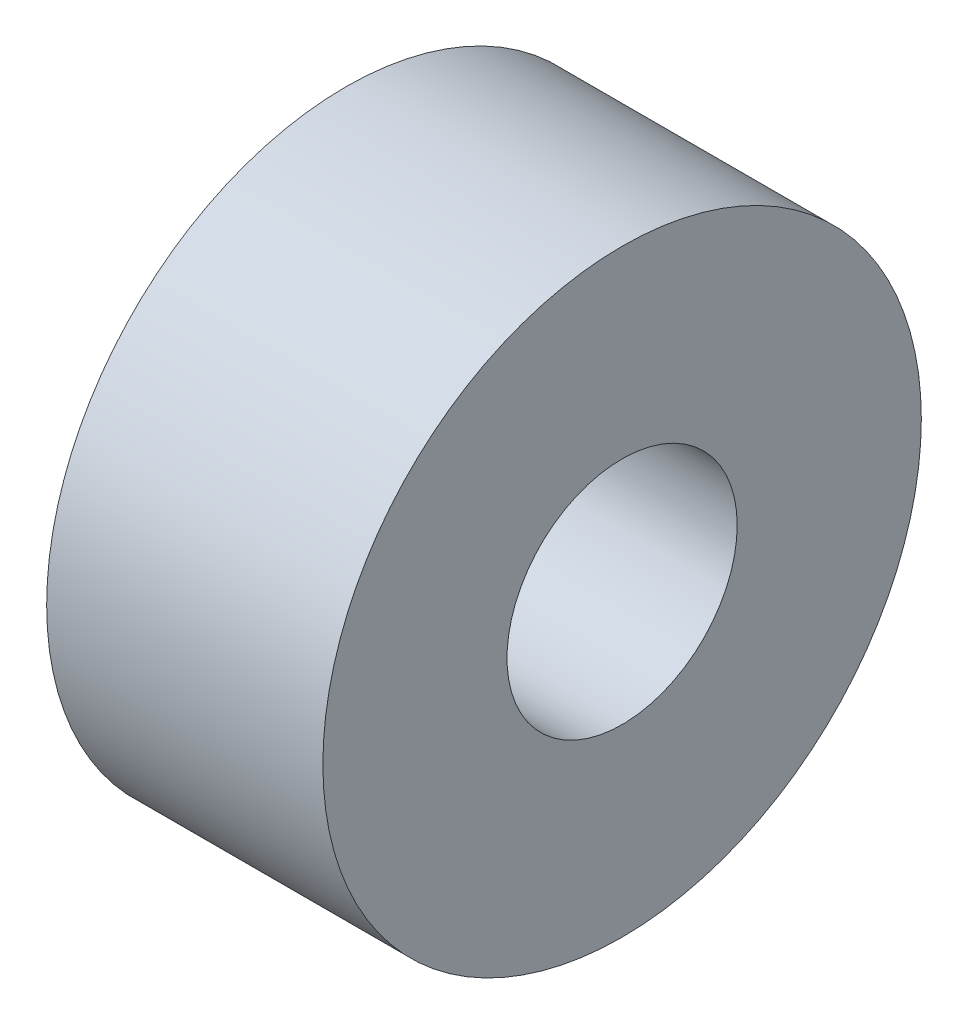
SolidWorks part; units mm, degrees
ref_plane "前视基准面" through (0, 0, 0) normal (0, 0, 1) x (1, 0, 0)
ref_plane "上视基准面" through (0, 0, 0) normal (0, 1, 0) x (1, 0, 0)
ref_plane "右视基准面" through (0, 0, 0) normal (1, 0, 0) x (0, 0, -1)
other "Configuration Table"
sketch "草图1" plane through (0, 0, 0) normal (1, 0, 0) x (0, 0, -1)
  circle A0 centre (0, 0) radius 25
  circle A1 centre (0, 0) radius 65
  dimension "D1" = 50
  dimension "D2" = 130
extrude "凸台-拉伸1" add sketch "草图1" along normal blind 60
ref_plane "基准面1" through (30, 0, 0) normal (1, 0, 0) x (0, 0, -1)
